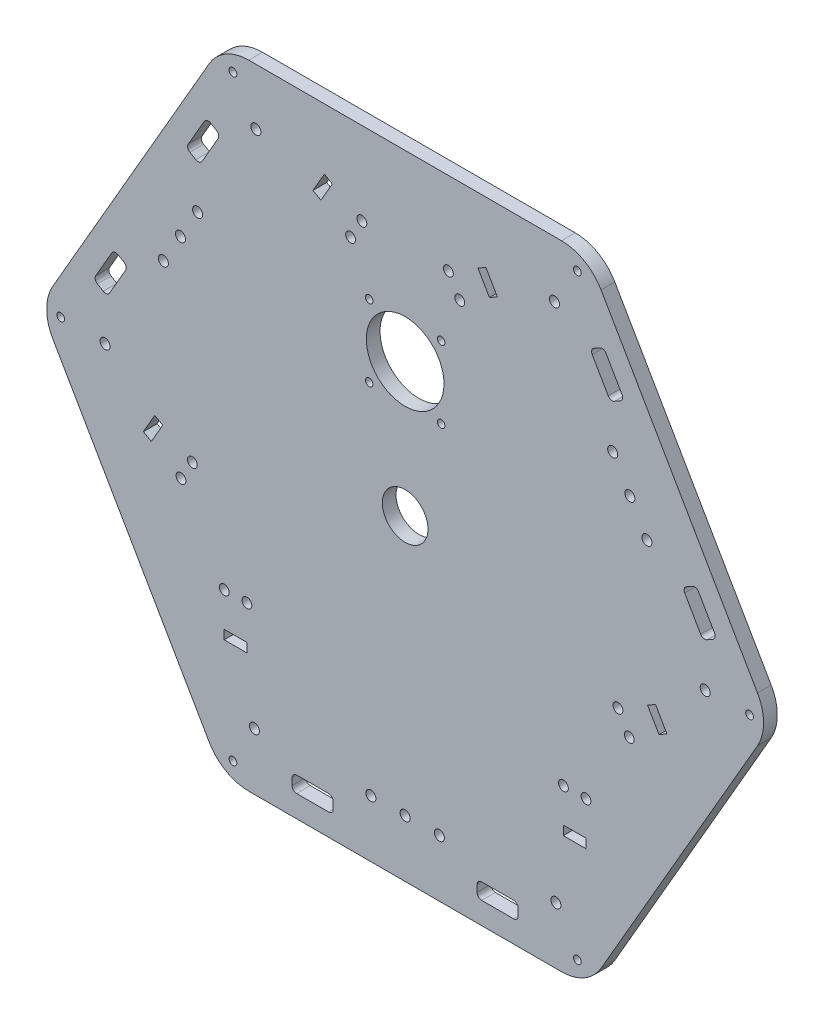
SolidWorks part; units mm, degrees
material "PP Homopolymer"
ref_plane "Front Plane" through (0, 0, 0) normal (0, 0, 1) x (1, 0, 0)
ref_plane "Top Plane" through (0, 0, 0) normal (0, 1, 0) x (1, 0, 0)
ref_plane "Right Plane" through (0, 0, 0) normal (1, 0, 0) x (0, 0, -1)
sketch "Sketch1" plane through (0, 0, 0) normal (0, 0, 1) x (1, 0, 0)
  line L1 (80, 138.5641) -> (-80, 138.5641)
  line L2 (-80, 138.5641) -> (-160, 0)
  line L3 (-160, 0) -> (-80, -138.5641)
  line L4 (-80, -138.5641) -> (80, -138.5641)
  line L5 (80, -138.5641) -> (160, 0)
  line L6 (160, 0) -> (80, 138.5641)
  circle A0 centre (0, 0) radius 138.5641 construction
  dimension "D1" = 160
extrude "Boss-Extrude1" add sketch "Sketch1" along normal blind 6
fillet "Fillet1" radius 20 6 edges at (80, 138.5641, 3) (-80, 138.5641, 3) (-160, 0, 3) (-80, -138.5641, 3) (80, -138.5641, 3) (160, 0, 3)
sketch "Sketch5" plane through (0, 0, 6) normal (0, 0, 1) x (1, 0, 0)
  line L0 (-66, -113.5641) -> (-15, -113.5641) construction
  line L1 (-68.453, -138.5641) -> (68.453, -138.5641) construction
  line L2 (0, 0) -> (0, -208.1146) construction
  line L3 (44.4949, 150.0607) -> (156.8007, -44.4587) construction
  line L4 (154.2265, 10) -> (85.7735, 128.5641) construction
  line L5 (0, 0) -> (201.4877, 116.3289) construction
  line L6 (-65.3494, 113.9397) -> (-90.8494, 69.7724) construction
  line L7 (131.3494, -0.3756) -> (105.8494, 43.7917) construction
  line L8 (0, 0) -> (-120, 69.282) construction
  line L9 (-85.7735, 128.5641) -> (-154.2265, 10) construction
  line L10 (-131.3494, -0.3756) -> (-65.3494, 113.9397) construction
  circle A0 centre (-66, -113.5641) radius 2.2
  circle A1 centre (-15, -113.5641) radius 2.2
  circle A2 centre (15, -113.5641) radius 2.2
  circle A3 centre (66, -113.5641) radius 2.2
  circle A4 centre (-65.3494, 113.9397) radius 2.2
  circle A5 centre (-90.8494, 69.7724) radius 2.2
  circle A6 centre (-105.8494, 43.7917) radius 2.2
  circle A7 centre (-131.3494, -0.3756) radius 2.2
  circle A8 centre (131.3494, -0.3756) radius 2.2
  circle A9 centre (105.8494, 43.7917) radius 2.2
  circle A10 centre (90.8494, 69.7724) radius 2.2
  circle A11 centre (65.3494, 113.9397) radius 2.2
  point P17 (120, 69.282)
  point P38 (0, 0)
  dimension "D1" = 4.4
  dimension "D2" = 4.4
  dimension "D3" = 51
  dimension "D4" = 25
  dimension "D5" = 15
  dimension "D6" = 25
  dimension "D7" = 120
extrude "Cut-Extrude3" cut sketch "Sketch5" against normal blind 10
sketch "Sketch6" plane through (0, 0, 6) normal (0, 0, 1) x (1, 0, 0)
  line L0 (-66, -113.5641) -> (-15, -113.5641) construction
  line L1 (-40.5, -113.5641) -> (-40.5, -131.821) construction
  line L2 (0, 138.5641) -> (0, -138.5641) construction
  line L3 (-49.5, -128.9641) -> (-31.5, -128.9641)
  line L4 (-49.5, -128.9641) -> (-49.5, -121.9641)
  line L5 (-49.5, -121.9641) -> (-31.5, -121.9641)
  line L6 (-31.5, -128.9641) -> (-31.5, -121.9641)
  line L7 (-49.5, -128.9641) -> (-31.5, -121.9641) construction
  line L8 (-49.5, -121.9641) -> (-31.5, -128.9641) construction
  line L9 (68.453, 138.5641) -> (-68.453, 138.5641) construction
  line L10 (-68.453, -138.5641) -> (68.453, -138.5641) construction
  line L11 (49.5, -121.9641) -> (31.5, -128.9641) construction
  line L12 (49.5, -128.9641) -> (31.5, -121.9641) construction
  line L13 (40.5, -113.5641) -> (40.5, -131.821) construction
  line L14 (66, -113.5641) -> (15, -113.5641) construction
  line L15 (31.5, -128.9641) -> (31.5, -121.9641)
  line L16 (49.5, -121.9641) -> (31.5, -121.9641)
  line L17 (49.5, -128.9641) -> (49.5, -121.9641)
  line L18 (49.5, -128.9641) -> (31.5, -128.9641)
  line L19 (-86.9362, 107.3503) -> (-95.9362, 91.7618)
  line L20 (-86.9362, 107.3503) -> (-80.874, 103.8503)
  line L21 (-80.874, 103.8503) -> (-89.874, 88.2618)
  line L22 (-95.9362, 91.7618) -> (-89.874, 88.2618)
  line L23 (-127.4362, 37.2022) -> (-121.374, 33.7022)
  line L24 (-130.374, 18.1138) -> (-121.374, 33.7022)
  line L25 (-136.4362, 21.6138) -> (-130.374, 18.1138)
  line L26 (-136.4362, 21.6138) -> (-127.4362, 37.2022)
  line L27 (-65.3494, 113.9397) -> (-90.8494, 69.7724) construction
  line L28 (-78.0994, 91.8561) -> (-93.9103, 100.9845) construction
  line L29 (120, -69.282) -> (-120, 69.282) construction
  line L30 (-86.9362, 107.3503) -> (-89.874, 88.2618) construction
  line L31 (-80.874, 103.8503) -> (-95.9362, 91.7618) construction
  line L32 (-130.374, 18.1138) -> (-127.4362, 37.2022) construction
  line L33 (-136.4362, 21.6138) -> (-121.374, 33.7022) construction
  line L34 (-118.5994, 21.708) -> (-134.4103, 30.8365) construction
  line L35 (-131.3494, -0.3756) -> (-105.8494, 43.7917) construction
  line L36 (136.4362, 21.6138) -> (127.4362, 37.2022)
  line L37 (136.4362, 21.6138) -> (130.374, 18.1138)
  line L38 (130.374, 18.1138) -> (121.374, 33.7022)
  line L39 (127.4362, 37.2022) -> (121.374, 33.7022)
  line L40 (95.9362, 91.7618) -> (89.874, 88.2618)
  line L41 (80.874, 103.8503) -> (89.874, 88.2618)
  line L42 (86.9362, 107.3503) -> (80.874, 103.8503)
  line L43 (86.9362, 107.3503) -> (95.9362, 91.7618)
  line L44 (131.3494, -0.3756) -> (105.8494, 43.7917) construction
  line L45 (118.5994, 21.708) -> (134.4103, 30.8365) construction
  line L46 (-120, -69.282) -> (120, 69.282) construction
  line L47 (136.4362, 21.6138) -> (121.374, 33.7022) construction
  line L48 (130.374, 18.1138) -> (127.4362, 37.2022) construction
  line L49 (80.874, 103.8503) -> (95.9362, 91.7618) construction
  line L50 (86.9362, 107.3503) -> (89.874, 88.2618) construction
  line L51 (78.0994, 91.8561) -> (93.9103, 100.9845) construction
  line L52 (65.3494, 113.9397) -> (90.8494, 69.7724) construction
  point P6 (-40.5, -125.4641)
  point P25 (40.5, -125.4641)
  point P33 (-88.4051, 97.8061)
  point P48 (-128.9051, 27.658)
  point P53 (128.9051, 27.658)
  point P68 (88.4051, 97.8061)
  point P69 (0, 0)
  dimension "D1" = 16.5
  dimension "D2" = 8.4
  dimension "D3" = 7
extrude "Cut-Extrude4" cut sketch "Sketch6" against normal blind 10
fillet "Fillet3" radius 2 24 edges at (-95.9362, 91.7618, 3) (-89.874, 88.2618, 3) (-86.9362, 107.3503, 3) (-80.874, 103.8503, 3) (-121.374, 33.7022, 3) (-127.4362, 37.2022, 3) (-130.374, 18.1138, 3) (-136.4362, 21.6138, 3) (-49.5, -128.9641, 3) (-49.5, -121.9641, 3) (-31.5, -128.9641, 3) (-31.5, -121.9641, 3) (49.5, -128.9641, 3) (49.5, -121.9641, 3) (31.5, -128.9641, 3) (31.5, -121.9641, 3) (136.4362, 21.6138, 3) (130.374, 18.1138, 3) (127.4362, 37.2022, 3) (121.374, 33.7022, 3) (80.874, 103.8503, 3) (89.874, 88.2618, 3) (86.9362, 107.3503, 3) (95.9362, 91.7618, 3)
sketch "Sketch9" plane through (0, 0, 6) normal (0, 0, 1) x (1, 0, 0)
  line L0 (-68.453, -138.5641) -> (68.453, -138.5641) construction
  line L1 (-78.453, -135.8846) -> (0, 0) construction
  line L2 (0, -138.5641) -> (0, 0) construction
  line L3 (-78.453, 135.8846) -> (0, 0) construction
  line L4 (-120, 69.282) -> (0, 0) construction
  line L5 (156.906, 0) -> (0, 0) construction
  line L6 (120, 69.282) -> (0, 0) construction
  circle A0 centre (-75.3812, -130.5641) radius 1.7
  arc A1 (-85.7735, -128.5641) -> (-68.453, -138.5641) centre (-68.453, -118.5641) ccw construction
  circle A2 centre (75.3812, -130.5641) radius 1.7
  circle A3 centre (-75.3812, 130.5641) radius 1.7
  circle A4 centre (-150.7624, 0) radius 1.7
  circle A5 centre (150.7624, 0) radius 1.7
  circle A6 centre (75.3812, 130.5641) radius 1.7
  point P28 (0, 0)
  dimension "D2" = 3.4
  dimension "D1" = 8
extrude "Cut-Extrude7" cut sketch "Sketch9" against normal blind 70
sketch "Sketch10" plane through (0, 0, 6) normal (0, 0, 1) x (1, 0, 0)
  line L0 (0, 138.5641) -> (0, -138.5641) construction
  line L1 (68.453, 138.5641) -> (-68.453, 138.5641) construction
  line L2 (-68.453, -138.5641) -> (68.453, -138.5641) construction
  line L3 (0, 0) -> (35.575, 0) construction
  line L4 (-35.575, -35.575) -> (35.575, -35.575) construction
  line L5 (-35.575, -35.575) -> (-35.575, 35.575) construction
  line L6 (-35.575, 35.575) -> (35.575, 35.575) construction
  line L7 (35.575, -35.575) -> (35.575, 35.575) construction
  line L8 (-35.575, -35.575) -> (35.575, 35.575) construction
  line L9 (-35.575, 35.575) -> (35.575, -35.575) construction
  line L10 (-35.575, -35.575) -> (35.575, -35.575) construction
  circle A0 centre (-35.575, 35.575) radius 2.25
  circle A1 centre (35.575, 35.575) radius 2.25
  circle A2 centre (35.575, -35.575) radius 2.25
  circle A3 centre (-35.575, -35.575) radius 2.25
  circle A4 centre (0, 0) radius 39
  point P6 (0, 0)
  dimension "D3" = 4.5
  dimension "D4" = 78
  dimension "D1" = 71.15
  dimension "D2" = 71.15
sketch "Sketch14" plane through (0, 0, 6) normal (0, 0, 1) x (1, 0, 0)
  circle A0 centre (0, 0) radius 10
  dimension "D1" = 20
extrude "Cut-Extrude10" cut sketch "Sketch14" against normal blind 43
sketch "Sketch15" plane through (0, 0, 6) normal (0, 0, 1) x (1, 0, 0)
  line L0 (-109.5799, -16.6699) -> (-106.1158, -18.6699)
  line L1 (-106.1158, -18.6699) -> (-111.1158, -27.3301)
  line L2 (-111.1158, -27.3301) -> (-114.5799, -25.3301)
  line L3 (-114.5799, -25.3301) -> (-109.5799, -16.6699)
  line L4 (-85.7735, 128.5641) -> (-154.2265, 10) construction
  line L5 (-120, 69.282) -> (-52.2537, 30.1687) construction
  line L6 (-35.3534, 111.8942) -> (-40.3534, 103.2339)
  line L7 (-31.8893, 109.8942) -> (-35.3534, 111.8942)
  line L8 (-36.8893, 101.2339) -> (-31.8893, 109.8942)
  line L9 (-40.3534, 103.2339) -> (-36.8893, 101.2339)
  line L10 (40.3534, 103.2339) -> (36.8893, 101.2339)
  line L11 (36.8893, 101.2339) -> (31.8893, 109.8942)
  line L12 (31.8893, 109.8942) -> (35.3534, 111.8942)
  line L13 (35.3534, 111.8942) -> (40.3534, 103.2339)
  line L14 (114.5799, -25.3301) -> (109.5799, -16.6699)
  line L15 (111.1158, -27.3301) -> (114.5799, -25.3301)
  line L16 (106.1158, -18.6699) -> (111.1158, -27.3301)
  line L17 (109.5799, -16.6699) -> (106.1158, -18.6699)
  line L18 (120, 69.282) -> (52.2537, 30.1687) construction
  line L19 (69.2265, -86.5641) -> (69.2265, -82.5641)
  line L20 (69.2265, -82.5641) -> (79.2265, -82.5641)
  line L21 (79.2265, -82.5641) -> (79.2265, -86.5641)
  line L22 (79.2265, -86.5641) -> (69.2265, -86.5641)
  line L23 (-79.2265, -86.5641) -> (-69.2265, -86.5641)
  line L24 (-79.2265, -82.5641) -> (-79.2265, -86.5641)
  line L25 (-69.2265, -82.5641) -> (-79.2265, -82.5641)
  line L26 (-69.2265, -86.5641) -> (-69.2265, -82.5641)
  line L27 (0, -138.5641) -> (0, -60.3374) construction
  point P35 (0, 0)
  dimension "D1" = 10
  dimension "D2" = 4
  dimension "D3" = 52
  dimension "D4" = 75
  dimension "D5" = 3
extrude "Cut-Extrude11" cut sketch "Sketch15" against normal blind 10
sketch "Sketch16" plane through (0, 0, 6) normal (0, 0, 1) x (1, 0, 0)
  line L8 (0, 0) -> (75.9573, 0) construction
  line L9 (0, 0) -> (0, 138.5641) construction
  line L10 (-15.75, 42.8141) -> (15.75, 74.3141) construction
  line L11 (-15.75, 74.3141) -> (15.75, 42.8141) construction
  line L12 (15.75, 74.3141) -> (15.75, 42.8141) construction
  line L13 (-15.75, 42.8141) -> (15.75, 42.8141) construction
  line L14 (-15.75, 74.3141) -> (-15.75, 42.8141) construction
  line L15 (-15.75, 74.3141) -> (15.75, 74.3141) construction
  circle A4 centre (15.75, 74.3141) radius 1.65
  circle A5 centre (-15.75, 74.3141) radius 1.65
  circle A6 centre (15.75, 42.8141) radius 1.65
  circle A7 centre (-15.75, 42.8141) radius 1.65
  circle A8 centre (0, 58.5641) radius 17
  point P37 (0, 58.5641)
  dimension "D1" = 34
extrude "Cut-Extrude12" cut sketch "Sketch16" against normal blind 10
sketch "Sketch19" plane through (0, 0, 6) normal (0, 0, 1) x (1, 0, 0)
  line L0 (-90.8494, 69.7724) -> (-105.8494, 43.7917) construction
  circle A0 centre (-98.3494, 56.782) radius 2.2
  circle A1 centre (98.3494, 56.782) radius 2.2
  circle A2 centre (0, -113.5641) radius 2.2
  point P13 (0, 0)
  dimension "D1" = 4.4
  dimension "D2" = 3
extrude "Cut-Extrude14" cut sketch "Sketch19" against normal blind 10
sketch "Sketch21" plane through (0, 0, 6) normal (0, 0, 1) x (1, 0, 0)
  line L0 (15, -113.5641) -> (66, -113.5641) construction
  line L1 (40.5, -113.5641) -> (40.5, -70.8741) construction
  line L2 (40.5, -113.5641) -> (40.5, -138.5641) construction
  line L3 (-68.453, -138.5641) -> (68.453, -138.5641) construction
  line L4 (0, 0) -> (0, -138.5641) construction
  line L5 (-40.5, -113.5641) -> (-40.5, -138.5641) construction
  line L6 (-40.5, -113.5641) -> (-40.5, -70.8741) construction
  line L7 (-15, -113.5641) -> (-66, -113.5641) construction
  line L8 (-105.8494, 43.7917) -> (-131.3494, -0.3756) construction
  line L9 (-118.5994, 21.708) -> (-81.6287, 0.363) construction
  line L10 (-118.5994, 21.708) -> (-140.25, 34.208) construction
  line L11 (-78.0994, 91.8561) -> (-99.75, 104.3561) construction
  line L12 (-78.0994, 91.8561) -> (-41.1287, 70.5111) construction
  line L13 (-90.8494, 69.7724) -> (-65.3494, 113.9397) construction
  line L14 (90.8494, 69.7724) -> (65.3494, 113.9397) construction
  line L15 (78.0994, 91.8561) -> (41.1287, 70.5111) construction
  line L16 (78.0994, 91.8561) -> (99.75, 104.3561) construction
  line L17 (118.5994, 21.708) -> (140.25, 34.208) construction
  line L18 (118.5994, 21.708) -> (81.6287, 0.363) construction
  line L19 (105.8494, 43.7917) -> (131.3494, -0.3756) construction
  line L20 (0, 0) -> (48.9357, 0) construction
  circle A0 centre (75.3812, -130.5641) radius 1.7 construction
  circle A1 centre (-75.3812, -130.5641) radius 1.7 construction
  circle A2 centre (-150.7624, 0) radius 1.7 construction
  circle A3 centre (-75.3812, 130.5641) radius 1.7 construction
  circle A4 centre (75.3812, 130.5641) radius 1.7 construction
  circle A5 centre (150.7624, 0) radius 1.7 construction
  point P52 (0, 0)
  dimension "D1" = 67.69
  dimension "D2" = 3
sketch "Sketch22" plane through (0, 0, 6) normal (0, 0, 1) x (1, 0, 0)
  line L0 (-81.6287, 0.363) -> (-41.1287, 70.5111)
  line L1 (-41.1287, 70.5111) -> (41.1287, 70.5111)
  line L2 (41.1287, 70.5111) -> (81.6287, 0.363)
  line L3 (81.6287, 0.363) -> (40.5, -70.8741)
  line L4 (40.5, -70.8741) -> (-40.5, -70.8741)
  line L5 (-40.5, -70.8741) -> (-81.6287, 0.363)
sketch "Sketch23" plane through (0, 0, 6) normal (0, 0, 1) x (1, 0, 0)
  line L0 (74.2265, -82.5641) -> (74.2265, -67.5641) construction
  line L1 (79.2265, -82.5641) -> (69.2265, -82.5641) construction
  line L2 (79.1765, -67.5641) -> (74.2265, -67.5641) construction
  line L3 (0, 0) -> (0, -138.5641) construction
  line L4 (-79.1765, -67.5641) -> (-74.2265, -67.5641) construction
  line L5 (-74.2265, -82.5641) -> (-74.2265, -67.5641) construction
  line L6 (-108.6158, -23) -> (-95.6254, -30.5) construction
  line L7 (-98.1004, -34.7868) -> (-95.6254, -30.5) construction
  line L8 (-18.9239, 102.3509) -> (-21.3989, 98.0641) construction
  line L9 (-34.3893, 105.5641) -> (-21.3989, 98.0641) construction
  line L10 (34.3893, 105.5641) -> (21.3989, 98.0641) construction
  line L11 (18.9239, 102.3509) -> (21.3989, 98.0641) construction
  line L12 (98.1004, -34.7868) -> (95.6254, -30.5) construction
  line L13 (108.6158, -23) -> (95.6254, -30.5) construction
  circle A0 centre (79.1765, -67.5641) radius 2.15
  circle A1 centre (69.2765, -67.5641) radius 2.15
  circle A2 centre (-69.2765, -67.5641) radius 2.15
  circle A3 centre (-79.1765, -67.5641) radius 2.15
  circle A4 centre (-98.1004, -34.7868) radius 2.15
  circle A5 centre (-93.1504, -26.2132) radius 2.15
  circle A6 centre (-23.8739, 93.7772) radius 2.15
  circle A7 centre (-18.9239, 102.3509) radius 2.15
  circle A8 centre (18.9239, 102.3509) radius 2.15
  circle A9 centre (23.8739, 93.7772) radius 2.15
  circle A10 centre (93.1504, -26.2132) radius 2.15
  circle A11 centre (98.1004, -34.7868) radius 2.15
  point P45 (0, 0)
  dimension "D1" = 4.3
  dimension "D2" = 4.95
  dimension "D3" = 15
  dimension "D4" = 3
extrude "Cut-Extrude15" cut sketch "Sketch23" against normal blind 10
